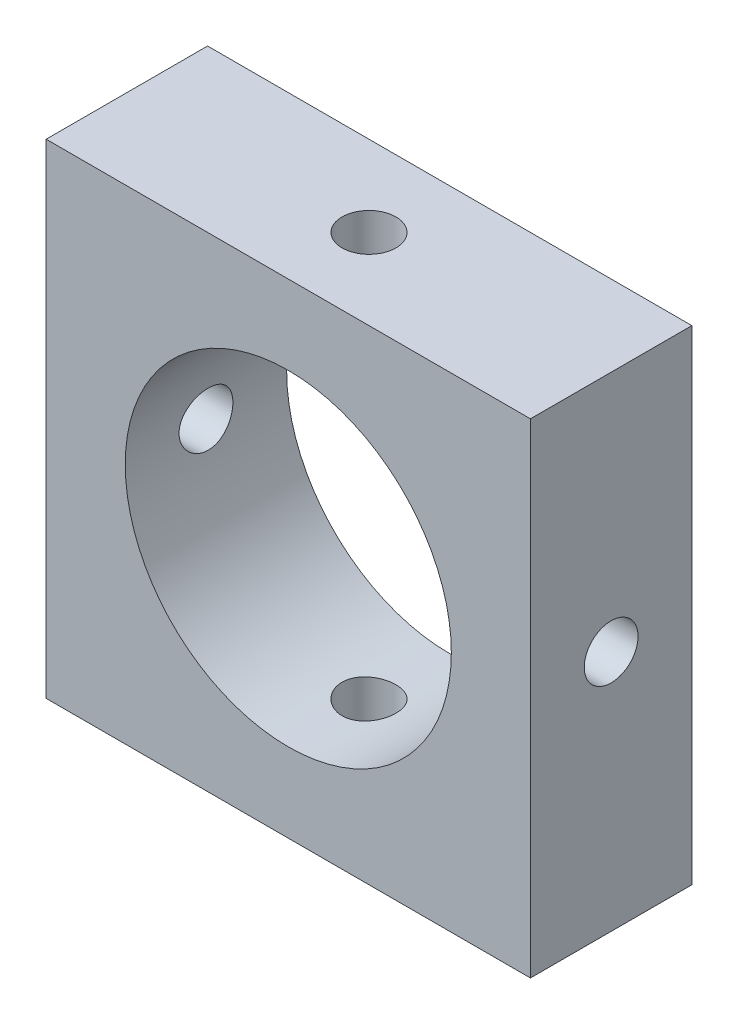
SolidWorks part; units mm, degrees
material "Balsa"
ref_plane "Front Plane" through (0, 0, 0) normal (0, 0, 1) x (1, 0, 0)
ref_plane "Top Plane" through (0, 0, 0) normal (0, 1, 0) x (1, 0, 0)
ref_plane "Right Plane" through (0, 0, 0) normal (1, 0, 0) x (0, 0, -1)
sketch "Sketch1" plane through (0, 0, 0) normal (0, 0, 1) x (1, 0, 0)
  line L1 (0, 0) -> (57.15, 0)
  line L2 (0, 0) -> (0, 57.15)
  line L3 (0, 57.15) -> (57.15, 57.15)
  line L4 (57.15, 0) -> (57.15, 57.15)
  dimension "D1" = 57.15
extrude "Boss-Extrude1" add sketch "Sketch1" along normal blind 19.05
sketch "Sketch2" plane through (0, 0, 0) normal (0, 0, -1) x (-1, 0, 0)
  line L0 (-57.15, 57.15) -> (0, 0) construction
  circle A0 centre (-28.575, 28.575) radius 19.2405
  point P6 (-28.575, 28.575)
  dimension "D1" = 38.481
extrude "Cut-Extrude1" cut sketch "Sketch2" against normal blind 19.05
sketch "Sketch5" plane through (57.15, 0, 0) normal (1, 0, 0) x (0, 0, -1)
  line L0 (0, 57.15) -> (-19.05, 0) construction
  circle A0 centre (-9.525, 28.575) radius 3.175
  point P6 (-9.525, 28.575)
  dimension "D1" = 6.35
extrude "Cut-Extrude2" cut sketch "Sketch5" against normal through all
sketch "Sketch6" plane through (0, 0, 0) normal (0, -1, 0) x (1, 0, 0)
  line L0 (57.15, 0) -> (0, 19.05) construction
  circle A0 centre (28.575, 9.525) radius 3.175
  point P6 (28.575, 9.525)
  dimension "D1" = 6.35
extrude "Cut-Extrude3" cut sketch "Sketch6" against normal through all
